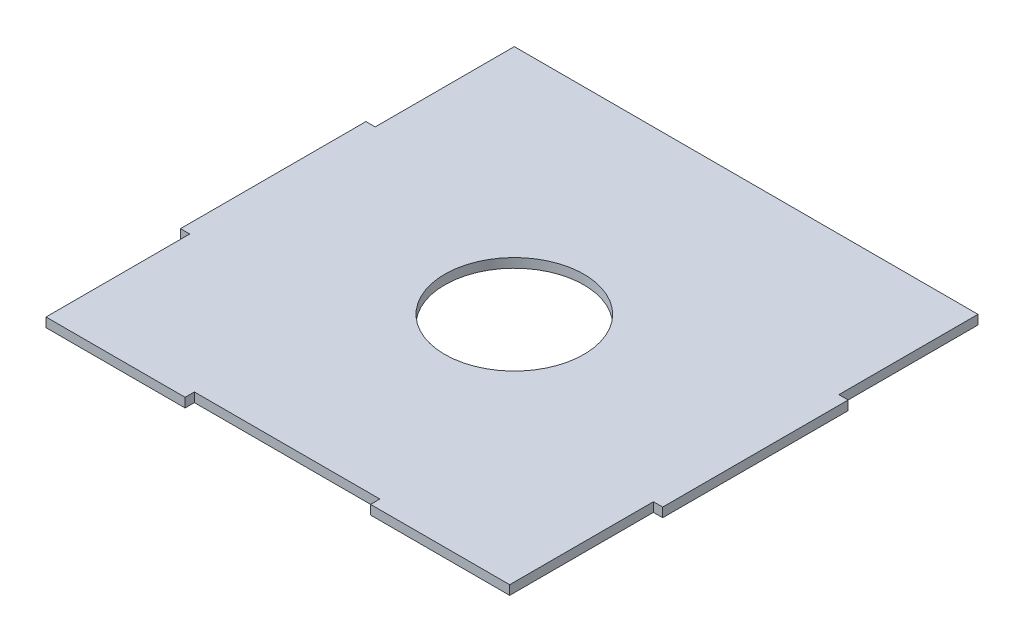
SolidWorks part; units mm, degrees
ref_plane "前视基准面" through (0, 0, 0) normal (0, 0, 1) x (1, 0, 0)
ref_plane "上视基准面" through (0, 0, 0) normal (0, 1, 0) x (1, 0, 0)
ref_plane "右视基准面" through (0, 0, 0) normal (1, 0, 0) x (0, 0, -1)
sketch "草图1" plane through (0, 0, 0) normal (0, 1, 0) x (1, 0, 0)
  line L0 (0, 0) -> (0, 100)
  line L1 (0, 0) -> (100, 0)
  line L2 (0, 100) -> (100, 100)
  line L3 (100, 0) -> (100, 100)
  line L4 (-2, 70) -> (0, 70)
  line L5 (-2, 70) -> (-2, 30)
  line L6 (0, 70) -> (0, 30)
  line L7 (-2, 30) -> (0, 30)
  line L8 (100, 70) -> (102, 70)
  line L9 (100, 70) -> (100, 30)
  line L10 (102, 70) -> (102, 30)
  line L11 (100, 30) -> (102, 30)
  line L12 (30, 0) -> (30, 1)
  line L13 (30, 0) -> (70, 0)
  line L14 (30, 1) -> (70, 1)
  line L15 (70, 0) -> (70, 1)
  line L16 (0, 0) -> (0, -1)
  line L17 (0, 0) -> (30, 0)
  line L18 (0, -1) -> (30, -1)
  line L19 (30, 0) -> (30, -1)
  line L20 (70, 0) -> (70, -1)
  line L21 (70, 0) -> (100, 0)
  line L22 (70, -1) -> (100, -1)
  line L23 (100, 0) -> (100, -1)
  circle A0 centre (50, 50) radius 15
  point P0 (0, 30)
  point P3 (0, 70)
  point P4 (-2, 30)
  point P5 (-2, 70)
  point P6 (100, 30)
  point P7 (100, 70)
  point P8 (102, 30)
  point P12 (102, 70)
extrude "凸台-拉伸1" add sketch "草图1" along normal blind 2 contours L5 L7 L0 L4 | L1 L3 L2 L0 | L3 L11 L10 L8 | L16 L17 L19 L18 | L20 L21 L23 L22
